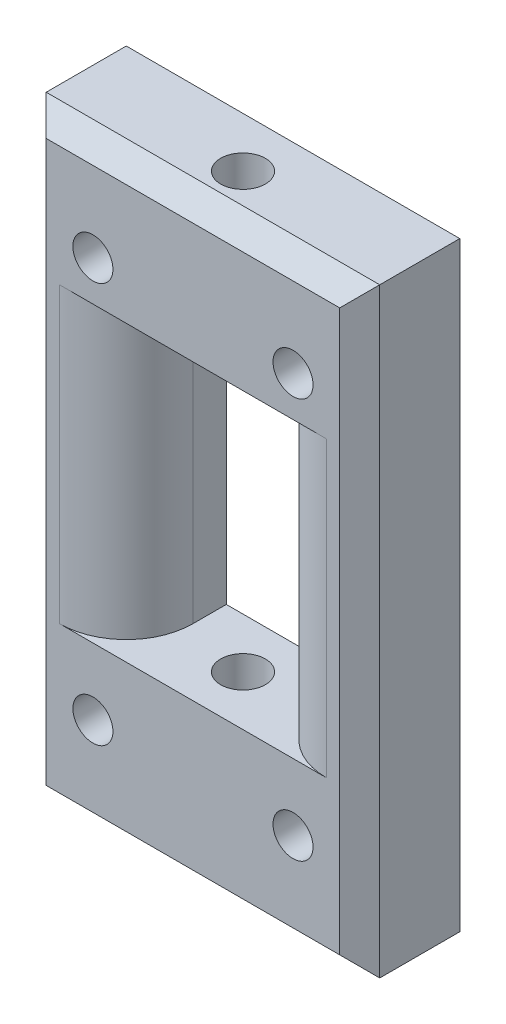
SolidWorks part; units mm, degrees
ref_plane "Front Plane" through (0, 0, 0) normal (0, 0, 1) x (1, 0, 0)
ref_plane "Top Plane" through (0, 0, 0) normal (0, 1, 0) x (1, 0, 0)
ref_plane "Right Plane" through (0, 0, 0) normal (1, 0, 0) x (0, 0, -1)
sketch "Sketch1" plane through (0, 0, 0) normal (0, 0, 1) x (1, 0, 0)
  line L4 (75, 95) -> (125, 95)
  line L5 (75, 95) -> (75, 5)
  line L6 (75, 5) -> (125, 5)
  line L7 (125, 95) -> (125, 5)
  line L8 (75, 95) -> (125, 5) construction
  line L9 (75, 5) -> (125, 95) construction
  circle A0 centre (115, 20) radius 3 construction
  circle A1 centre (85, 20) radius 3 construction
  circle A2 centre (115, 80) radius 3 construction
  circle A3 centre (85, 80) radius 3 construction
  circle A4 centre (115, 20) radius 3
  circle A5 centre (85, 20) radius 3
  circle A6 centre (115, 80) radius 3
  circle A7 centre (85, 80) radius 3
  point P14 (100, 50)
extrude "Boss-Extrude1" add sketch "Sketch1" along normal blind 15
sketch "Sketch2" plane through (0, 95, 0) normal (0, 1, 0) x (1, 0, 0)
  circle A0 centre (100, -7.5) radius 3.35
extrude "Cut-Extrude1" cut sketch "Sketch2" against normal through all
sketch "Sketch3" plane through (0, 0, 15) normal (0, 0, 1) x (1, 0, 0)
  line L0 (90, 70) -> (90, 74)
  line L2 (110, 70) -> (110, 30)
  line L3 (110, 30) -> (90, 30)
  line L12 (90, 30) -> (90, 70)
  line L14 (90, 74) -> (110, 74)
  line L15 (110, 74) -> (110, 70)
extrude "Cut-Extrude2" cut sketch "Sketch3" against normal through all
chamfer "Chamfer1" distance 3 angle 45 4 edges at (100, 5, 15) (125, 50, 15) (100, 95, 15) (75, 50, 15)
fillet "Fillet1" radius 10 2 edges at (90, 52, 15) (110, 52, 15)
